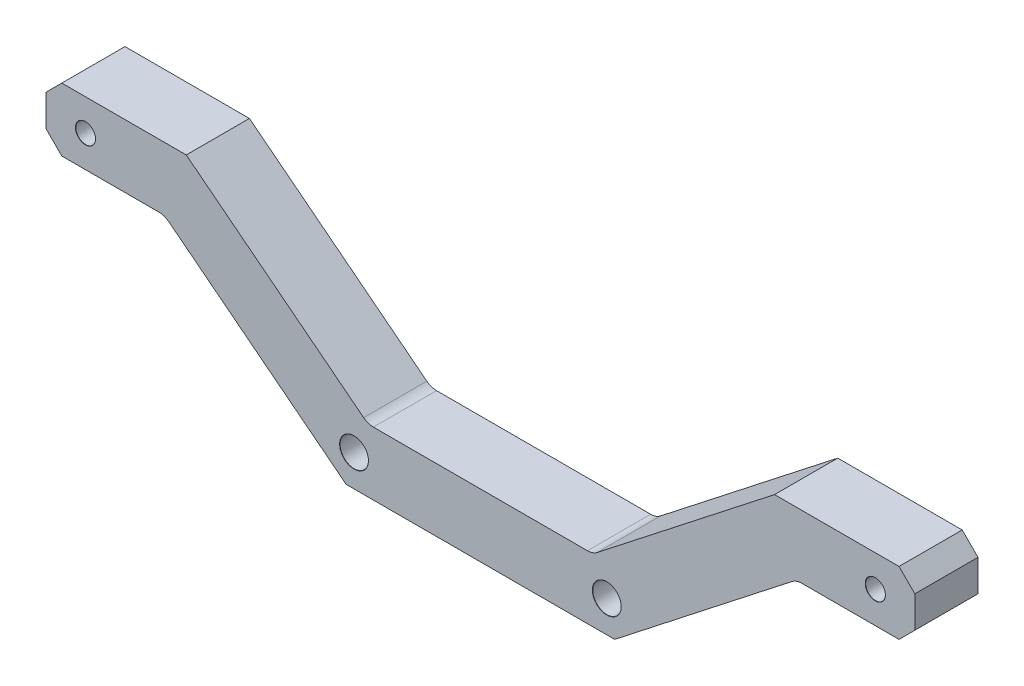
SolidWorks part; units mm, degrees
ref_plane "Front Plane" through (0, 0, 0) normal (0, 0, 1) x (1, 0, 0)
ref_plane "Top Plane" through (0, 0, 0) normal (0, 1, 0) x (1, 0, 0)
ref_plane "Right Plane" through (0, 0, 0) normal (1, 0, 0) x (0, 0, -1)
sketch "Sketch1" plane through (0, 0, 0) normal (0, 0, 1) x (1, 0, 0)
  line L0 (0, 26.9567) -> (0, -27.8705) construction
  line L1 (-16, 0) -> (16, 0) construction
  line L2 (-14.2417, 4) -> (14.2417, 4)
  line L3 (14.2417, 4) -> (37.2417, 22)
  line L4 (37.2417, 22) -> (55, 22)
  line L5 (55, 22) -> (55, 14)
  line L6 (55, 14) -> (40, 14)
  line L7 (40, 14) -> (17, -4)
  line L8 (17, -4) -> (-17, -4)
  line L9 (-40, 14) -> (-17, -4)
  line L10 (17, 17.3271) -> (17, -12.307) construction
  line L11 (40, 30.546) -> (40, 9.818) construction
  line L12 (-55, 14) -> (-40, 14)
  line L13 (-55, 22) -> (-55, 14)
  line L14 (-37.2417, 22) -> (-55, 22)
  line L15 (-14.2417, 4) -> (-37.2417, 22)
  circle A0 centre (16, 0) radius 1
  circle A1 centre (50, 18) radius 1
  circle A2 centre (-50, 18) radius 1
  circle A3 centre (-16, 0) radius 1
  point P14 (0, 4)
  point P23 (55, 18)
  point P33 (0, -4)
  dimension "D2" = 2
  dimension "D5" = 2
  dimension "D1" = 32
  dimension "D3" = 8
  dimension "D4" = 8
  dimension "D6" = 18
  dimension "D7" = 40
  dimension "D8" = 8
  dimension "D9" = 5
  dimension "D10" = 10
extrude "Boss-Extrude1" add sketch "Sketch1" along normal blind 8
hole_wizard "Tap Drill for M3x0.5 Tap1" positions "Sketch2" profile "Sketch3" hole size "M3x0.5" standard "ANSI Metric" end condition through all
sketch "Sketch2" plane through (0, 0, 8) normal (0, 0, 1) x (1, 0, 0)
  point P0 (50, 18)
  point P3 (-50, 18)
sketch "Sketch3" plane through (50, 18, 8) normal (1, 0, 0) x (0, -1, 0)
  line L0 (0, 0) -> (0, 8)
  line L1 (0, 8) -> (1.25, 8)
  line L2 (1.25, 8) -> (1.25, 0.025)
  line L3 (1.25, 0.025) -> (1.275, 0)
  line L5 (1.275, 0) -> (0, 0)
  line L6 (-1.25, 0.025) -> (-1.275, 0) construction
  line L11 (0, -6.35) -> (0, 107.95) construction
  dimension "Thru Hole Dia." = 2.5
  dimension "Thru Hole Depth" = 8
  dimension "Near C'Sink Dia." = 2.55
  dimension "Near C'Sink Angle" = 90
hole_wizard "M3 Clearance Hole1" positions "Sketch4" profile "Sketch5" hole size "M3" standard "ANSI Metric" end condition through all
sketch "Sketch4" plane through (0, 0, 8) normal (0, 0, 1) x (1, 0, 0)
  point P0 (-16, 0)
  point P3 (16, 0)
sketch "Sketch5" plane through (-16, 0, 8) normal (1, 0, 0) x (0, -1, 0)
  line L0 (0, 0) -> (0, 8)
  line L1 (0, 8) -> (1.8, 8)
  line L2 (1.8, 8) -> (1.8, 0.025)
  line L3 (1.8, 0.025) -> (1.825, 0)
  line L5 (1.825, 0) -> (0, 0)
  line L6 (-1.8, 0.025) -> (-1.825, 0) construction
  line L11 (0, -6.35) -> (0, 107.95) construction
  dimension "Thru Hole Dia." = 3.6
  dimension "Thru Hole Depth" = 8
  dimension "Near C'Sink Dia." = 3.65
  dimension "Near C'Sink Angle" = 90
chamfer "Chamfer3" distance 2 angle 45 4 edges at (-55, 14, 4) (-55, 22, 4) (55, 14, 4) (55, 22, 4)
fillet "Fillet1" radius 2 4 edges at (-40, 14, 4) (40, 14, 4) (14.2417, 4, 4) (-14.2417, 4, 4)
